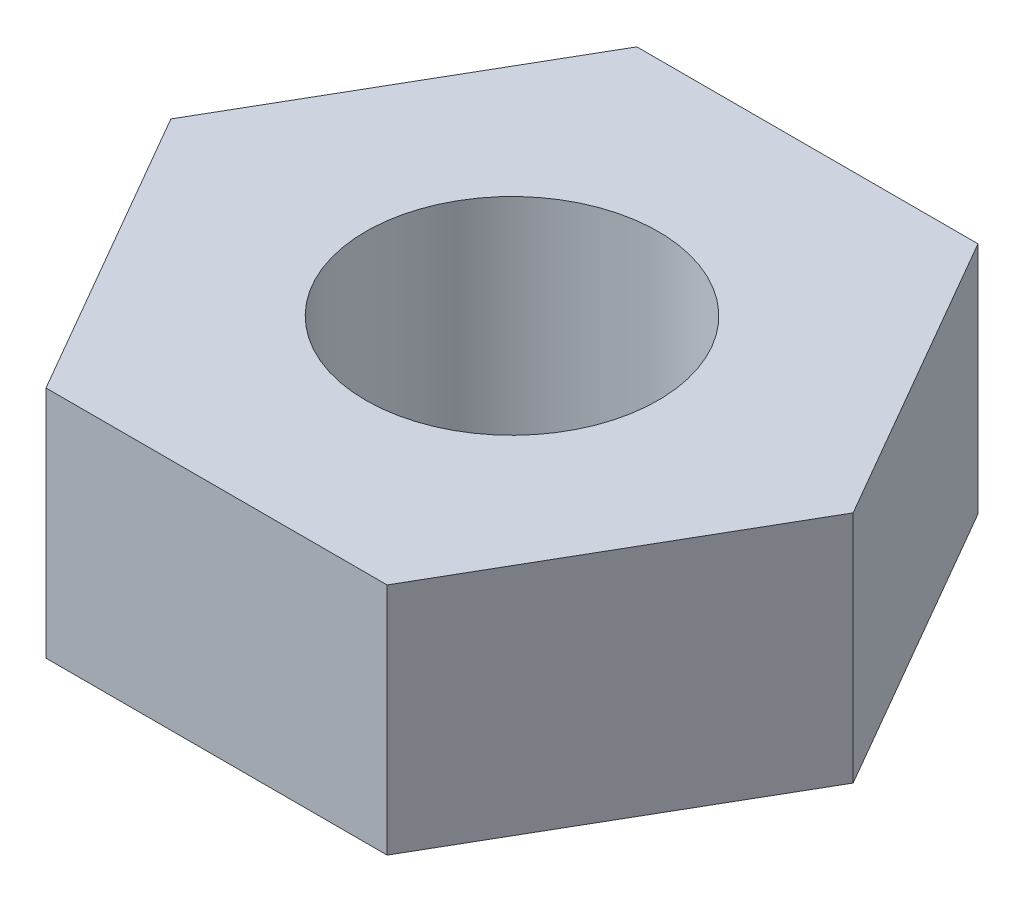
SolidWorks part; units mm, degrees
material "Nylon 101"
ref_plane "Front Plane" through (0, 0, 0) normal (0, 0, 1) x (1, 0, 0)
ref_plane "Top Plane" through (0, 0, 0) normal (0, 1, 0) x (1, 0, 0)
ref_plane "Right Plane" through (0, 0, 0) normal (1, 0, 0) x (0, 0, -1)
sketch "Sketch1" plane through (0, 0, 0) normal (0, 1, 0) x (1, 0, 0)
  line L1 (2.9156, 0) -> (1.4578, 2.525)
  line L2 (1.4578, 2.525) -> (-1.4578, 2.525)
  line L3 (-1.4578, 2.525) -> (-2.9156, 0)
  line L4 (-2.9156, 0) -> (-1.4578, -2.525)
  line L5 (-1.4578, -2.525) -> (1.4578, -2.525)
  line L6 (1.4578, -2.525) -> (2.9156, 0)
  circle A0 centre (0, 0) radius 2.525 construction
  circle A1 centre (0, 0) radius 1.25
  point P10 (0, 0)
  dimension "D2" = 2.5
  dimension "D1" = 5.05
extrude "Boss-Extrude1" add sketch "Sketch1" along normal blind 2
